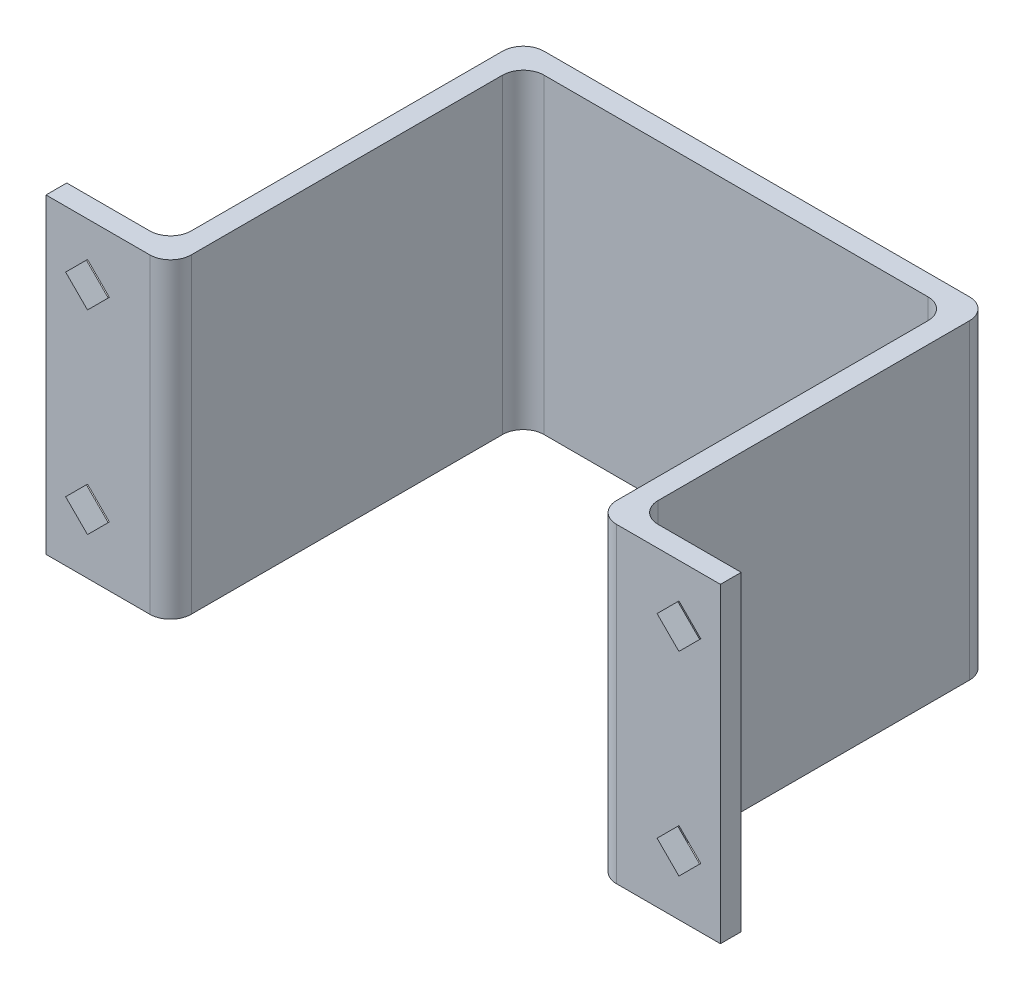
SolidWorks part; units mm, degrees
ref_plane "Front Plane" through (0, 0, 0) normal (0, 0, 1) x (1, 0, 0)
ref_plane "Top Plane" through (0, 0, 0) normal (0, 1, 0) x (1, 0, 0)
ref_plane "Right Plane" through (0, 0, 0) normal (1, 0, 0) x (0, 0, -1)
sketch "Sketch1" plane through (0, 0, 0) normal (0, 0, 1) x (1, 0, 0)
  line L1 (0, 0) -> (57.15, 0)
  line L2 (0, 0) -> (0, 38.1)
  line L3 (0, 38.1) -> (57.15, 38.1)
  line L4 (57.15, 0) -> (57.15, 38.1)
  dimension "D1" = 38.1
  dimension "D2" = 57.15
extrude "Boss-Extrude1" add sketch "Sketch1" along normal blind 2.54
sketch "Sketch2" plane through (0, 0, 2.54) normal (0, 0, 1) x (1, 0, 0)
  line L0 (0, 0) -> (57.15, 0) construction
  line L1 (0, 38.1) -> (2.54, 38.1)
  line L2 (0, 38.1) -> (0, 0)
  line L3 (0, 0) -> (2.54, 0)
  line L4 (2.54, 38.1) -> (2.54, 0)
  line L5 (28.575, 38.1) -> (28.575, 0.4246) construction
  line L6 (57.15, 38.1) -> (0, 38.1) construction
  line L7 (54.61, 38.1) -> (54.61, 0)
  line L8 (57.15, 0) -> (54.61, 0)
  line L9 (57.15, 38.1) -> (57.15, 0)
  line L10 (57.15, 38.1) -> (54.61, 38.1)
  dimension "D1" = 2.54
extrude "Boss-Extrude2" add sketch "Sketch2" along normal blind 43.18
sketch "Sketch3" plane through (57.15, 0, 0) normal (1, 0, 0) x (0, 0, -1)
  line L0 (-45.72, 0) -> (0, 0) construction
  line L1 (-45.72, 38.1) -> (-43.18, 38.1)
  line L2 (-45.72, 38.1) -> (-45.72, 0)
  line L3 (-45.72, 0) -> (-43.18, 0)
  line L4 (-43.18, 38.1) -> (-43.18, 0)
  dimension "D1" = 2.54
extrude "Boss-Extrude3" add sketch "Sketch3" along normal blind 12.7
sketch "Sketch4" plane through (0, 0, 0) normal (-1, 0, 0) x (0, 0, 1)
  line L5 (45.72, 0) -> (0, 0) construction
  line L6 (45.72, 38.1) -> (43.18, 38.1)
  line L7 (45.72, 38.1) -> (45.72, 0)
  line L8 (45.72, 0) -> (43.18, 0)
  line L9 (43.18, 38.1) -> (43.18, 0)
  dimension "D1" = 2.54
extrude "Boss-Extrude4" add sketch "Sketch4" along normal blind 12.7
fillet "Fillet1" radius 2.54 8 edges at (54.61, 19.05, 2.54) (2.54, 19.05, 2.54) (2.54, 19.05, 45.72) (54.61, 19.05, 45.72) (57.15, 19.05, 43.18) (0, 19.05, 43.18) (0, 19.05, 0) (57.15, 19.05, 0)
sketch "Sketch5" plane through (0, 0, 43.18) normal (0, 0, -1) x (-1, 0, 0)
  line L0 (-64.77, 38.1) -> (-64.77, 0) construction
  line L1 (-69.85, 38.1) -> (-59.69, 38.1) construction
  line L2 (-69.85, 0) -> (-59.69, 0) construction
  line L3 (-64.77, 0) -> (-64.77, 35.5955) construction
  line L4 (-64.77, 33.8002) -> (-67.4461, 31.1241)
  line L17 (-67.4461, 31.1241) -> (-64.77, 28.448)
  line L18 (-64.77, 28.448) -> (-62.0939, 31.1241)
  line L19 (-62.0939, 31.1241) -> (-64.77, 33.8002)
  line L28 (-64.77, 9.9877) -> (-67.4461, 7.3116)
  line L29 (-67.4461, 7.3116) -> (-64.77, 4.6355)
  line L30 (-64.77, 4.6355) -> (-62.0939, 7.3116)
  line L31 (-62.0939, 7.3116) -> (-64.77, 9.9877)
  line L32 (-64.77, 20.5105) -> (-62.0939, 23.1866) [skipped]
  line L33 (-62.0939, 23.1866) -> (-64.77, 25.8627) [skipped]
  line L34 (-64.77, 25.8627) -> (-67.4461, 23.1866) [skipped]
  line L35 (-67.4461, 23.1866) -> (-64.77, 20.5105) [skipped]
  line L36 (-62.0939, 15.2491) -> (-64.77, 17.9252) [skipped]
  line L37 (-64.77, 12.573) -> (-62.0939, 15.2491) [skipped]
  line L38 (-67.4461, 15.2491) -> (-64.77, 12.573) [skipped]
  line L39 (-64.77, 17.9252) -> (-67.4461, 15.2491) [skipped]
  line L40 (-69.85, 19.05) -> (16.7447, 19.05) construction
  line L41 (-69.85, 0) -> (-69.85, 38.1) construction
  line L42 (-28.575, 38.1) -> (-28.575, 0) construction
  line L43 (-54.61, 38.1) -> (-2.54, 38.1) construction
  line L44 (-2.54, 0) -> (-54.61, 0) construction
  line L45 (4.9439, 7.3116) -> (7.62, 9.9877)
  line L46 (7.62, 4.6355) -> (4.9439, 7.3116)
  line L47 (10.2961, 7.3116) -> (7.62, 4.6355)
  line L48 (7.62, 9.9877) -> (10.2961, 7.3116)
  line L49 (4.9439, 31.1241) -> (7.62, 33.8002)
  line L50 (7.62, 28.448) -> (4.9439, 31.1241)
  line L51 (10.2961, 31.1241) -> (7.62, 28.448)
  line L52 (7.62, 33.8002) -> (10.2961, 31.1241)
  dimension "D1" = 4
  dimension "D2" = 3.7846
  dimension "D3" = 9.398
extrude "Cut-Extrude1" cut sketch "Sketch5" against normal through all
